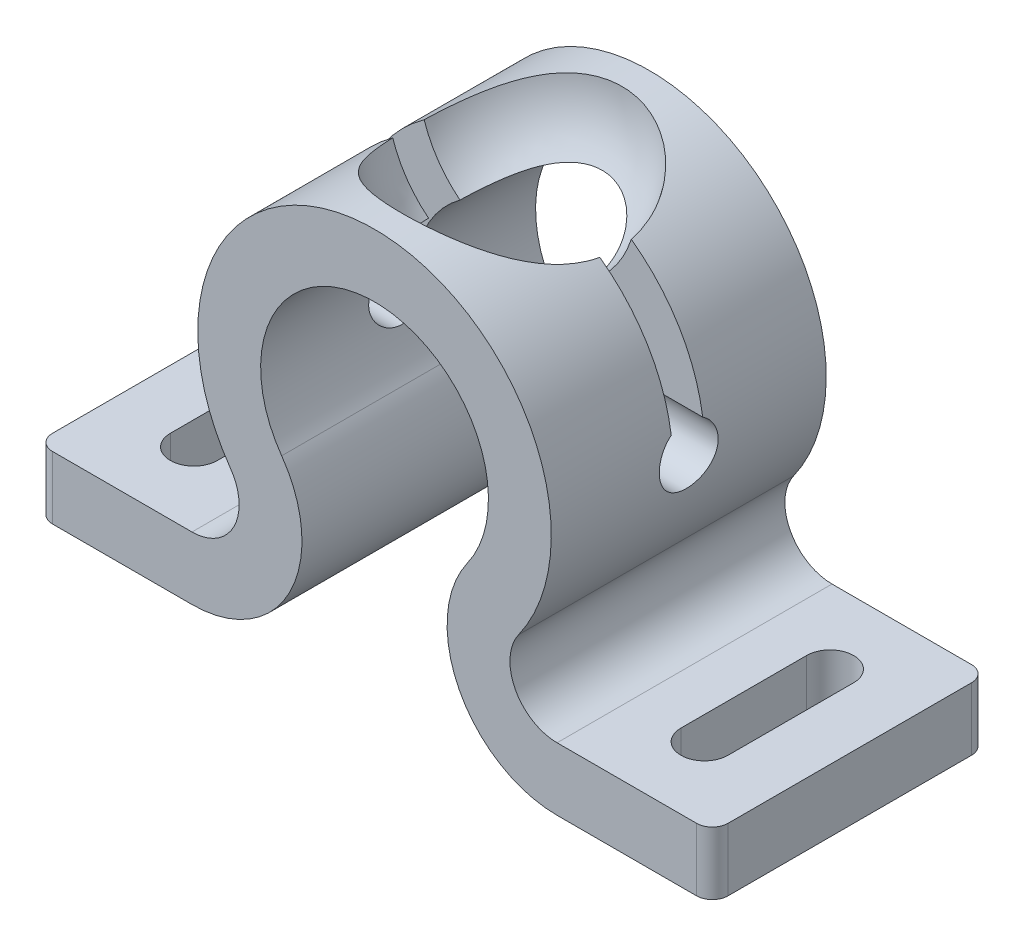
SolidWorks part; units mm, degrees
ref_plane "Front Plane" through (0, 0, 0) normal (0, 0, 1) x (1, 0, 0)
ref_plane "Top Plane" through (0, 0, 0) normal (0, 1, 0) x (1, 0, 0)
ref_plane "Right Plane" through (0, 0, 0) normal (1, 0, 0) x (0, 0, -1)
sketch "Sketch1" plane through (0, 0, 0) normal (0, 0, 1) x (1, 0, 0)
  line L0 (0, 0) -> (0, 90) construction
  line L1 (-86, 0) -> (-46.4758, 0)
  line L2 (46.4758, 0) -> (86, 0)
  arc A0 (23.6456, 44.2105) -> (-23.6456, 44.2105) centre (0, 61) ccw
  arc A1 (23.6456, 44.2105) -> (46.4758, 0) centre (46.4758, 28) ccw
  arc A2 (-46.4758, 0) -> (-23.6456, 44.2105) centre (-46.4758, 28) ccw
  point P11 (-47.9558, 30.1903)
  dimension "D2" = 58
  dimension "D3" = 28
  dimension "D4" = 56
  dimension "D1" = 172
  dimension "D5" = 90
  dimension "D6" = 86
extrude "Extrude-Thin1" add sketch "Sketch1" along normal blind 70 thin contours L2 A1 A0 A2 L1 thin type one direction reverse wall 16
sketch "Sketch3" plane through (86, 0, 0) normal (1, 0, 0) x (0, 0, -1)
  line L0 (-35, 0) -> (-35, 61) construction
  line L1 (-70, 0) -> (0, 0) construction
  line L4 (-39, 67.3443) -> (-39, 116)
  line L5 (-39, 116) -> (-31, 116)
  line L6 (-31, 67.3443) -> (-31, 116)
  arc A0 (-39, 67.3443) -> (-31, 67.3443) centre (-35, 61) ccw
  dimension "D1" = 15
  dimension "D2" = 61
  dimension "D3" = 55
  dimension "D4" = 4
  dimension "D5" = 4
extrude "Cut-Extrude1" cut sketch "Sketch3" against normal through all
sketch "Sketch4" plane through (0, 16, 0) normal (0, 1, 0) x (1, 0, 0)
  line L0 (0, 0) -> (0, -70) construction
  line L1 (-45, -70) -> (45, -70) construction
  line L2 (-86, -35) -> (86, -35) construction
  line L3 (-86, -70) -> (-86, 0) construction
  line L4 (86, -70) -> (86, 0) construction
  line L5 (-65, -35) -> (-65, -19) construction
  line L6 (-59, -19) -> (-59, -51)
  line L7 (-71, -19) -> (-71, -51)
  line L8 (71, -19) -> (71, -51)
  line L9 (59, -19) -> (59, -51)
  arc A0 (-59, -19) -> (-71, -19) centre (-65, -19) ccw
  arc A1 (-59, -51) -> (-71, -51) centre (-65, -51) cw
  arc A2 (59, -51) -> (71, -51) centre (65, -51) ccw
  arc A3 (59, -19) -> (71, -19) centre (65, -19) cw
  point P18 (-59, -35)
  point P20 (-71, -35)
  dimension "D1" = 6
  dimension "D2" = 16
  dimension "D3" = 65
extrude "Cut-Extrude2" cut sketch "Sketch4" against normal through all
ref_plane "Plane1" through (0, 0, 35) normal (0, 0, 1) x (1, 0, 0)
sketch "Sketch6" plane through (0, 0, 35) normal (0, 0, 1) x (1, 0, 0)
  line L0 (0, 134) -> (0, 78)
  arc A1 (0, 134) -> (0, 78) centre (0, 106) ccw
  dimension "D2" = 56
  dimension "D1" = 106
revolve "Cut-Revolve1" cut sketch "Sketch6" angle 360 about L0
fillet "Fillet1" radius 4 4 edges at (86, 8, 70) (86, 8, 0) (-86, 8, 70) (-86, 8, 0)
